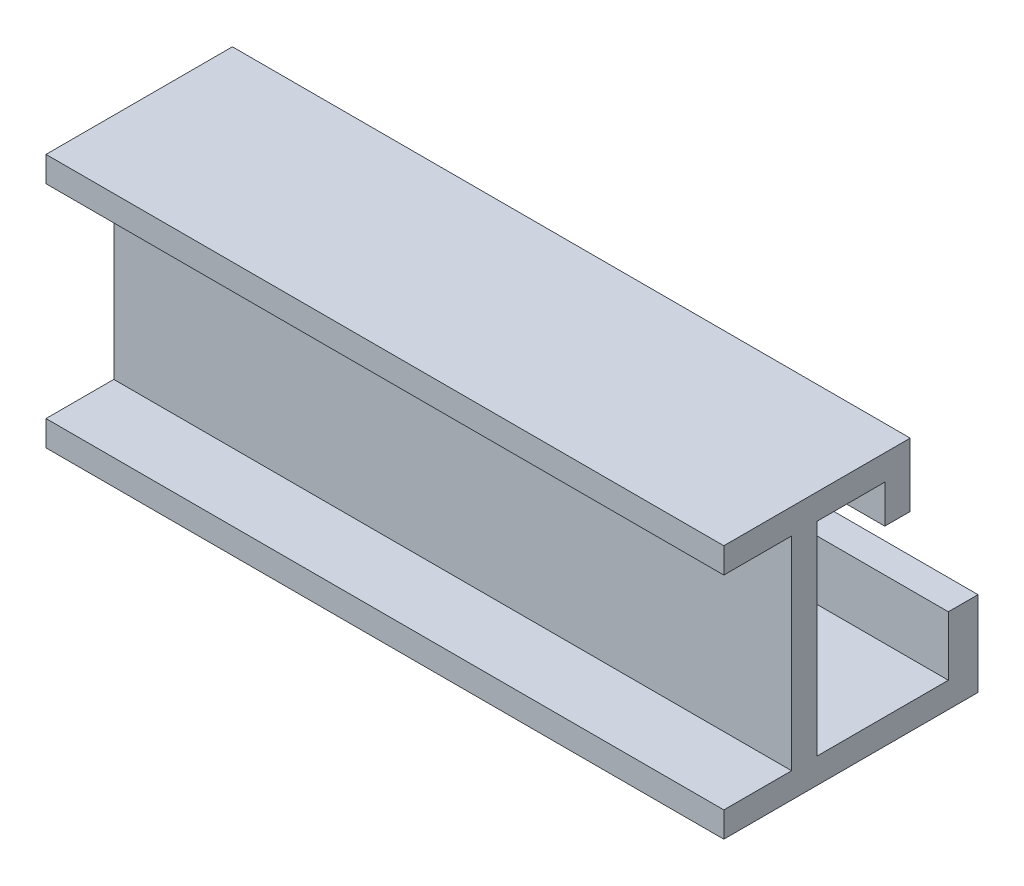
SolidWorks part; units mm, degrees
ref_plane "Спереди" through (0, 0, 0) normal (0, 0, 1) x (1, 0, 0)
ref_plane "Сверху" through (0, 0, 0) normal (0, 1, 0) x (1, 0, 0)
ref_plane "Справа" through (0, 0, 0) normal (1, 0, 0) x (0, 0, -1)
sketch "Эскиз1" plane through (0, 0, 0) normal (1, 0, 0) x (0, 0, -1)
  line L0 (-14, 24) -> (-8, 24) construction
  line L1 (-30, -30) -> (30, -30)
  line L2 (-30, -30) -> (-30, 30)
  line L3 (-30, 30) -> (30, 30)
  line L4 (30, -30) -> (30, 30)
  line L5 (-30, -30) -> (30, 30) construction
  line L6 (-30, 30) -> (30, -30) construction
  line L7 (-14, -24) -> (-30, -24)
  line L8 (-14, -24) -> (-14, 24)
  line L9 (-14, 24) -> (-30, 24)
  line L10 (-30, -24) -> (-30, 24)
  line L11 (-14, -24) -> (-30, 24) construction
  line L12 (-14, 24) -> (-30, -24) construction
  line L13 (8, -24) -> (-8, -24)
  line L14 (8, -24) -> (8, 24)
  line L15 (8, 24) -> (-8, 24)
  line L16 (-8, -24) -> (-8, 24)
  line L17 (8, -24) -> (-8, 24) construction
  line L18 (8, 24) -> (-8, -24) construction
  line L19 (-14, 24) -> (-14, 30) construction
  line L20 (23, -24) -> (23, -10)
  line L21 (8, -24) -> (23, -24)
  line L22 (8, 15) -> (14, 15)
  line L23 (14, 15) -> (14, 30)
  line L24 (23, -10) -> (30, -10)
  point P0 (0, 0)
  point P6 (-22, 0)
  point P11 (0, 0)
  dimension "D1" = 60
  dimension "D2" = 60
  dimension "D3" = 16
  dimension "D4" = 6
  dimension "D5" = 16
  dimension "D6" = 15
  dimension "D7" = 15
  dimension "D8" = 20
extrude "Бобышка-Вытянуть1" add sketch "Эскиз1" along normal mid plane 160
